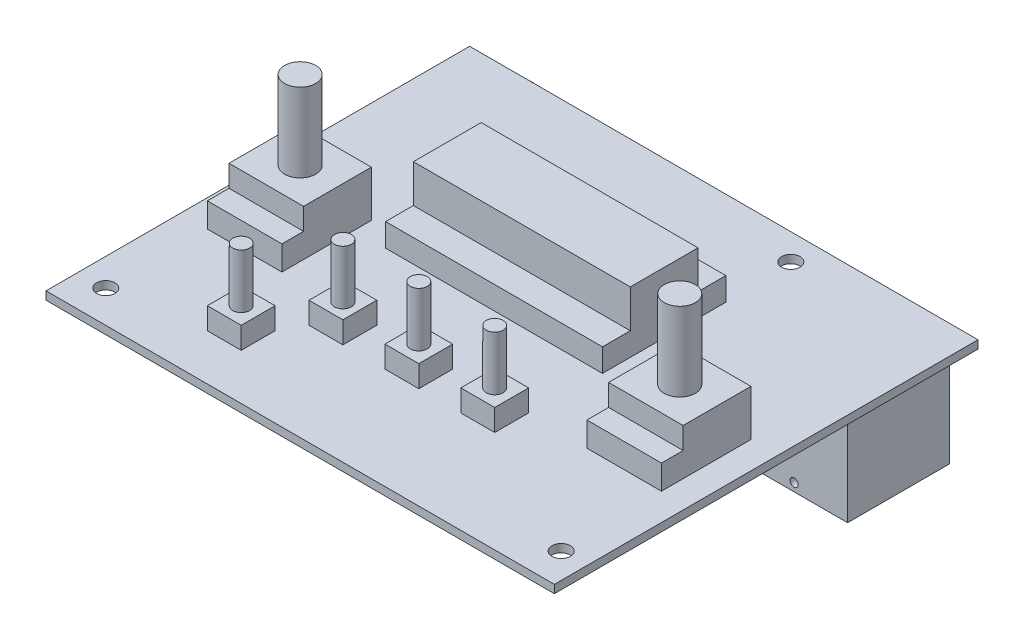
SolidWorks part; units mm, degrees
ref_plane "Front Plane" through (0, 0, 0) normal (0, 0, 1) x (1, 0, 0)
ref_plane "Top Plane" through (0, 0, 0) normal (0, 1, 0) x (1, 0, 0)
ref_plane "Right Plane" through (0, 0, 0) normal (1, 0, 0) x (0, 0, -1)
sketch "Sketch1" plane through (0, 0, 0) normal (0, 1, 0) x (1, 0, 0)
  line L1 (-47.625, 39.6875) -> (47.625, 39.6875)
  line L2 (-47.625, 39.6875) -> (-47.625, -39.6875)
  line L3 (-47.625, -39.6875) -> (47.625, -39.6875)
  line L4 (47.625, 39.6875) -> (47.625, -39.6875)
  line L5 (-47.625, 39.6875) -> (47.625, -39.6875) construction
  line L6 (-47.625, -39.6875) -> (47.625, 39.6875) construction
  point P0 (0, 0)
  dimension "D1" = 95.25
  dimension "D2" = 79.375
extrude "Boss-Extrude1" add sketch "Sketch1" along normal blind 1.524
hole_wizard "#29 (0.136) Diameter Hole1" positions "Sketch2" profile "Sketch3" hole size "#29" standard "ANSI Inch" end condition through all
sketch "Sketch2" plane through (0, 1.524, 0) normal (0, 1, 0) x (1, 0, 0)
  line L0 (47.625, -39.6875) -> (47.625, 39.6875) construction
  line L1 (-47.625, -39.6875) -> (47.625, -39.6875) construction
  line L2 (-47.625, 39.6875) -> (-47.625, -39.6875) construction
  line L3 (47.625, 39.6875) -> (-47.625, 39.6875) construction
  point P0 (42.8498, -33.6423)
  point P2 (17.4498, 34.7853)
  point P4 (-25.8318, 22.2123)
  point P6 (-42.4688, -33.6423)
  dimension "D1" = 4.7752
  dimension "D2" = 6.0452
  dimension "D3" = 6.0452
  dimension "D4" = 5.1562
  dimension "D5" = 30.1752
  dimension "D6" = 4.9022
  dimension "D7" = 17.4752
  dimension "D8" = 21.7932
sketch "Sketch3" plane through (42.8498, 1.524, 33.6423) normal (1, 0, 0) x (0, 0, 1)
  line L0 (0, 0) -> (0, 1.524)
  line L1 (0, 1.524) -> (1.7272, 1.524)
  line L2 (1.7272, 1.524) -> (1.7272, 0)
  line L5 (1.7272, 0) -> (0, 0)
  line L11 (0, -6.35) -> (0, 107.95) construction
  dimension "Thru Hole Dia." = 3.4544
  dimension "Thru Hole Depth" = 1.524
sketch "Sketch4" plane through (0, 1.524, 0) normal (0, 1, 0) x (1, 0, 0)
  line L0 (47.625, -39.6875) -> (47.625, 39.6875) construction
  line L1 (28.575, 2.2225) -> (42.545, 2.2225)
  line L2 (28.575, 2.2225) -> (28.575, -14.5415)
  line L3 (28.575, -14.5415) -> (42.545, -14.5415)
  line L4 (42.545, 2.2225) -> (42.545, -14.5415)
  line L5 (28.575, 2.2225) -> (42.545, -14.5415) construction
  line L6 (28.575, -14.5415) -> (42.545, 2.2225) construction
  line L7 (-47.625, -39.6875) -> (47.625, -39.6875) construction
  line L9 (-28.575, 2.2225) -> (-42.545, 2.2225)
  line L10 (-28.575, 2.2225) -> (-28.575, -14.5415)
  line L11 (-28.575, -14.5415) -> (-42.545, -14.5415)
  line L12 (-42.545, 2.2225) -> (-42.545, -14.5415)
  line L13 (-28.575, 2.2225) -> (-42.545, -14.5415) construction
  line L14 (-28.575, -14.5415) -> (-42.545, 2.2225) construction
  line L15 (-47.625, 39.6875) -> (-47.625, -39.6875) construction
  point P0 (35.56, -6.1595)
  point P9 (-35.56, -6.1595)
  dimension "D1" = 16.764
  dimension "D2" = 13.97
  dimension "D3" = 19.05
  dimension "D4" = 41.91
  dimension "D5" = 41.91
  dimension "D6" = 19.05
extrude "Boss-Extrude2" add sketch "Sketch4" along normal blind 4.572
sketch "Sketch5" plane through (0, 6.096, 0) normal (0, 1, 0) x (1, 0, 0)
  line L0 (-28.575, -14.5415) -> (-28.575, 2.2225) construction
  line L1 (-42.545, 2.2225) -> (-28.575, 2.2225)
  line L2 (-42.545, 2.2225) -> (-42.545, -10.4775)
  line L3 (-42.545, -10.4775) -> (-28.575, -10.4775)
  line L4 (-28.575, 2.2225) -> (-28.575, -10.4775)
  line L5 (42.545, -14.5415) -> (42.545, 2.2225) construction
  line L6 (28.575, 2.2225) -> (42.545, 2.2225)
  line L7 (28.575, 2.2225) -> (28.575, -10.4775)
  line L8 (28.575, -10.4775) -> (42.545, -10.4775)
  line L9 (42.545, 2.2225) -> (42.545, -10.4775)
  line L10 (0, 39.6875) -> (0, -39.6875) construction
  line L11 (47.625, 39.6875) -> (-47.625, 39.6875) construction
  line L12 (-47.625, -39.6875) -> (47.625, -39.6875) construction
  line L33 (-42.545, 2.2225) -> (-42.545, -14.5415) construction
  dimension "D1" = 12.7
extrude "Boss-Extrude3" add sketch "Sketch5" along normal blind 4.064
sketch "Sketch8" plane through (0, 1.524, 0) normal (0, 1, 0) x (1, 0, 0)
  line L0 (0, 39.6875) -> (0, -39.6875) construction
  line L1 (47.625, 39.6875) -> (-47.625, 39.6875) construction
  line L2 (-47.625, -39.6875) -> (47.625, -39.6875) construction
  line L3 (-47.625, 39.6875) -> (-47.625, -39.6875) construction
  line L5 (-26.035, -31.0515) -> (-19.685, -31.0515)
  line L6 (-26.035, -31.0515) -> (-26.035, -24.7015)
  line L7 (-26.035, -24.7015) -> (-19.685, -24.7015)
  line L8 (-3.175, -14.2875) -> (3.175, -20.6375) construction
  line L9 (-3.175, -20.6375) -> (3.175, -14.2875) construction
  line L10 (17.399, -14.2875) -> (17.399, -20.6375)
  line L11 (11.049, -14.2875) -> (17.399, -14.2875)
  line L12 (11.049, -14.2875) -> (11.049, -20.6375)
  line L13 (11.049, -20.6375) -> (17.399, -20.6375)
  line L14 (3.175, -14.2875) -> (3.175, -20.6375)
  line L15 (-3.175, -14.2875) -> (3.175, -14.2875)
  line L16 (-3.175, -14.2875) -> (-3.175, -20.6375)
  line L17 (-3.175, -20.6375) -> (3.175, -20.6375)
  line L18 (-11.049, -14.2875) -> (-11.049, -20.6375)
  line L19 (-17.399, -14.2875) -> (-11.049, -14.2875)
  line L20 (-17.399, -14.2875) -> (-17.399, -20.6375)
  line L21 (-17.399, -20.6375) -> (-11.049, -20.6375)
  line L22 (-19.685, -31.0515) -> (-19.685, -24.7015)
  line L23 (-26.035, -31.0515) -> (-19.685, -24.7015) construction
  line L24 (-26.035, -24.7015) -> (-19.685, -31.0515) construction
  point P6 (0, -17.4625)
  point P13 (-22.86, -27.8765)
  dimension "D1" = 30.226
  dimension "D2" = 58.674
  dimension "D3" = 6.35
  dimension "D4" = 53.975
  dimension "D5" = 27.94
  dimension "D6" = 14.986
extrude "Boss-Extrude5" add sketch "Sketch8" along normal blind 4.064
sketch "Sketch9" plane through (0, 5.588, 0) normal (0, 1, 0) x (1, 0, 0)
  line L0 (-17.399, -14.2875) -> (-11.049, -20.6375) construction
  line L1 (-3.175, -14.2875) -> (3.175, -20.6375) construction
  line L2 (11.049, -14.2875) -> (17.399, -20.6375) construction
  line L3 (-26.035, -24.7015) -> (-19.685, -31.0515) construction
  circle A0 centre (-13.9422, -17.7443) radius 1.5875
  circle A1 centre (0, -17.4625) radius 1.5875
  circle A2 centre (14.224, -17.4625) radius 1.5875
  circle A3 centre (-22.86, -27.8765) radius 1.5875
  dimension "D1" = 3.175
extrude "Boss-Extrude6" add sketch "Sketch9" along normal blind 10.16
sketch "Sketch10" plane through (0, 10.16, 0) normal (0, 1, 0) x (1, 0, 0)
  line L0 (-42.545, 2.2225) -> (-28.575, -10.4775) construction
  line L1 (28.575, 2.2225) -> (42.545, -10.4775) construction
  circle A0 centre (-35.56, -4.1275) radius 2.921
  circle A1 centre (35.56, -4.1275) radius 2.921
  dimension "D1" = 5.842
extrude "Boss-Extrude7" add sketch "Sketch10" along normal blind 14.732
sketch "Sketch11" plane through (0, 0, -39.6875) normal (0, 0, -1) x (-1, 0, 0)
  line L0 (-47.625, 0) -> (47.625, 0) construction
  line L1 (-42.2402, 0) -> (-22.225, 0)
  line L2 (-42.2402, 0) -> (-42.2402, -21.336)
  line L3 (-42.2402, -21.336) -> (-22.225, -21.336)
  line L4 (-22.225, 0) -> (-22.225, -21.336)
  line L5 (-47.625, 1.524) -> (-47.625, 0) construction
  dimension "D1" = 25.4
  dimension "D2" = 20.0152
  dimension "D3" = 21.336
extrude "Boss-Extrude8" add sketch "Sketch11" against normal blind 19.05 separate body
sketch "Sketch12" plane through (0, 0, -39.6875) normal (0, 0, -1) x (-1, 0, 0)
  line L0 (-32.2326, 0) -> (-32.2326, -21.336) construction
  line L1 (-22.225, 0) -> (-42.2402, 0) construction
  line L2 (-42.2402, -21.336) -> (-22.225, -21.336) construction
  circle A0 centre (-32.2326, -10.541) radius 6.985
  dimension "D1" = 13.97
  dimension "D2" = 10.795
extrude "Cut-Extrude1" cut sketch "Sketch12" against normal blind 3.175
hole_wizard "#53 (0.0595) Diameter Hole1" positions "Sketch13" profile "Sketch14" hole size "#53" standard "ANSI Inch" end condition through all
sketch "Sketch13" plane through (0, 0, -39.6875) normal (0, 0, -1) x (-1, 0, 0)
  line L1 (-32.2326, -10.541) -> (-32.2326, -21.336) construction
  line L2 (-42.2402, -21.336) -> (-22.225, -21.336) construction
  line L3 (-23.4886, -5.4927) -> (-32.2326, -10.541) construction
  line L5 (-40.9765, -5.4927) -> (-32.2326, -10.541) construction
  line L7 (-22.225, -21.336) -> (-22.225, 0) construction
  line L8 (-42.2402, 0) -> (-42.2402, -21.336) construction
  point P0 (-40.9765, -5.4927)
  point P2 (-23.4886, -5.4927)
  point P14 (-32.2326, -19.8183)
  dimension "D1" = 1.5176
  dimension "D2" = 120
  dimension "D3" = 120
  dimension "D4" = 1.2637
  dimension "D5" = 1.2637
sketch "Sketch14" plane through (40.9765, -5.4927, -39.6875) normal (1, 0, 0) x (0, 1, 0)
  line L0 (0, 0) -> (0, 79.375)
  line L1 (0, 79.375) -> (0.7556, 79.375)
  line L2 (0.7556, 79.375) -> (0.7556, 0)
  line L5 (0.7556, 0) -> (0, 0)
  line L11 (0, -6.35) -> (0, 107.95) construction
  dimension "Thru Hole Dia." = 1.5113
  dimension "Thru Hole Depth" = 79.375
sketch "Sketch15" plane through (0, 0, -39.6875) normal (0, 0, -1) x (-1, 0, 0)
  line L0 (-47.625, 0) -> (47.625, 0) construction
  line L1 (34.925, 0) -> (40.894, 0)
  line L2 (34.925, 0) -> (34.925, -5.334)
  line L3 (34.925, -5.334) -> (40.894, -5.334)
  line L4 (40.894, 0) -> (40.894, -5.334)
  line L5 (47.625, 1.524) -> (47.625, 0) construction
  dimension "D1" = 5.969
  dimension "D2" = 5.334
  dimension "D3" = 12.7
extrude "Boss-Extrude9" add sketch "Sketch15" against normal blind 13.97
sketch "Sketch16" plane through (0, 0, -39.6875) normal (0, 0, -1) x (-1, 0, 0)
  line L0 (34.925, 0) -> (40.894, -5.334) construction
  circle A0 centre (37.9095, -2.667) radius 1.778
  circle A1 centre (37.9095, -2.667) radius 2.54
  dimension "D1" = 5.08
  dimension "D2" = 3.556
extrude "Boss-Extrude10" add sketch "Sketch16" along normal blind 2.032 draft 9
sketch "Sketch17" plane through (0, 0, -39.6875) normal (0, 0, -1) x (-1, 0, 0)
  circle A0 centre (37.9095, -2.667) radius 1.778
extrude "Cut-Extrude2" cut sketch "Sketch17" against normal blind 12.7
sketch "Sketch18" plane through (0, 1.524, 0) normal (0, 1, 0) x (1, 0, 0)
  line L0 (-47.625, 39.6875) -> (-47.625, -39.6875) construction
  line L1 (-22.733, -0.9525) -> (17.907, -0.9525)
  line L2 (-22.733, -0.9525) -> (-22.733, 22.1615)
  line L3 (-22.733, 22.1615) -> (17.907, 22.1615)
  line L4 (17.907, -0.9525) -> (17.907, 22.1615)
  line L5 (47.625, 39.6875) -> (-47.625, 39.6875) construction
  dimension "D1" = 40.64
  dimension "D2" = 23.114
  dimension "D3" = 65.532
  dimension "D4" = 40.64
extrude "Boss-Extrude11" add sketch "Sketch18" along normal blind 4.318
sketch "Sketch19" plane through (0, 5.842, 0) normal (0, 1, 0) x (1, 0, 0)
  line L0 (-22.733, 22.1615) -> (17.907, -0.9525) construction
  line L1 (17.907, -0.9525) -> (17.907, 22.1615) construction
  line L2 (-22.733, 4.2545) -> (17.907, 4.2545)
  line L3 (-22.733, 4.2545) -> (-22.733, 16.9545)
  line L4 (-22.733, 16.9545) -> (17.907, 16.9545)
  line L5 (17.907, 4.2545) -> (17.907, 16.9545)
  line L6 (-22.733, 4.2545) -> (17.907, 16.9545) construction
  line L7 (-22.733, 16.9545) -> (17.907, 4.2545) construction
  point P4 (-2.413, 10.6045)
  dimension "D1" = 12.7
extrude "Boss-Extrude12" add sketch "Sketch19" along normal blind 7.112
sketch "Sketch20" plane through (0, 0, 0) normal (0, -1, 0) x (1, 0, 0)
  line L0 (-47.625, 39.6875) -> (47.625, 39.6875) construction
  line L1 (17.653, 35.8775) -> (-15.367, 35.8775)
  line L2 (17.653, 35.8775) -> (17.653, 33.4675)
  line L3 (17.653, 33.4675) -> (-15.367, 33.4675)
  line L4 (-15.367, 35.8775) -> (-15.367, 33.4675)
  line L5 (47.625, 39.6875) -> (47.625, -39.6875) construction
  dimension "D1" = 33.02
  dimension "D2" = 2.41
  dimension "D3" = 3.81
  dimension "D4" = 29.972
extrude "Boss-Extrude13" add sketch "Sketch20" along normal blind 2.54
sketch "Sketch21" plane through (0, 0, 0) normal (0, -1, 0) x (1, 0, 0)
  line L0 (47.625, -39.6875) -> (-34.925, -39.6875) construction
  line L1 (3.429, -39.6875) -> (-5.461, -39.6875)
  line L2 (3.429, -39.6875) -> (3.429, -35.1155)
  line L3 (3.429, -35.1155) -> (-5.461, -35.1155)
  line L4 (-5.461, -39.6875) -> (-5.461, -35.1155)
  line L5 (47.625, 39.6875) -> (47.625, -39.6875) construction
  dimension "D1" = 8.89
  dimension "D2" = 4.572
  dimension "D3" = 53.086
extrude "Boss-Extrude14" add sketch "Sketch21" along normal blind 4.826
sketch "Sketch22" plane through (0, 0, -39.6875) normal (0, 0, -1) x (-1, 0, 0)
  line L0 (-3.429, 0) -> (5.461, -4.826) construction
  line L1 (5.461, -4.826) -> (5.461, 0) construction
  line L2 (-3.429, -3.429) -> (5.461, -3.429)
  line L3 (-3.429, -3.429) -> (-3.429, -1.397)
  line L4 (-3.429, -1.397) -> (5.461, -1.397)
  line L5 (5.461, -3.429) -> (5.461, -1.397)
  line L6 (-3.429, -3.429) -> (5.461, -1.397) construction
  line L7 (-3.429, -1.397) -> (5.461, -3.429) construction
  point P4 (1.016, -2.413)
  dimension "D1" = 2.032
extrude "Boss-Extrude15" add sketch "Sketch22" along normal blind 1.524
